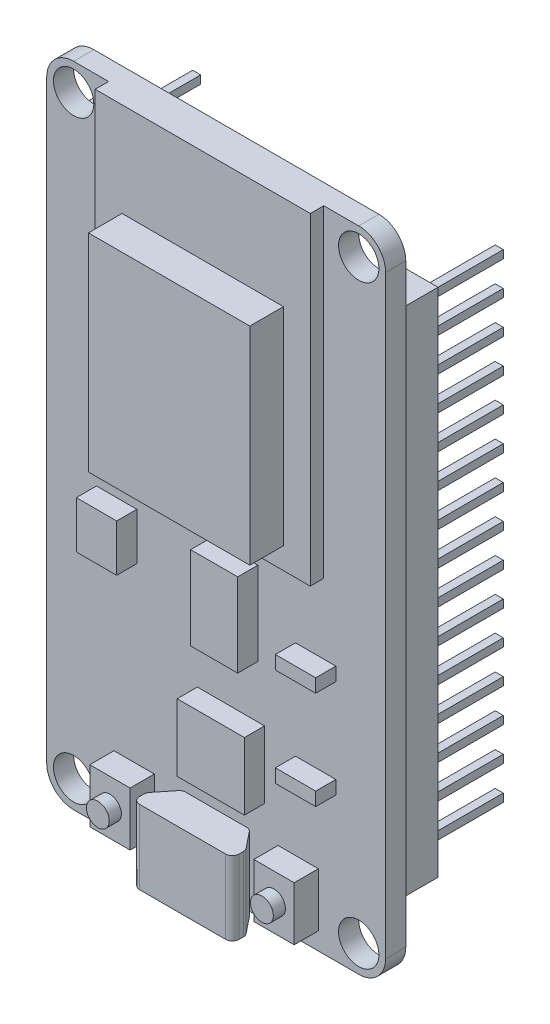
SolidWorks part; units mm, degrees
ref_plane "Plan de face" through (0, 0, 0) normal (0, 0, 1) x (1, 0, 0)
ref_plane "Plan de dessus" through (0, 0, 0) normal (0, 1, 0) x (1, 0, 0)
ref_plane "Plan de droite" through (0, 0, 0) normal (1, 0, 0) x (0, 0, -1)
sketch "Esquisse1" plane through (0, 0, 0) normal (0, 0, 1) x (1, 0, 0)
  line L1 (-10.6, -24.1) -> (10.6, -24.1)
  line L2 (-12.6, -22.1) -> (-12.6, 22.1)
  line L3 (-10.6, 24.1) -> (10.6, 24.1)
  line L4 (12.6, -22.1) -> (12.6, 22.1)
  line L5 (-12.6, -24.1) -> (12.6, 24.1) construction
  line L6 (-12.6, 24.1) -> (12.6, -24.1) construction
  arc A0 (-10.6, -24.1) -> (-12.6, -22.1) centre (-10.6, -22.1) cw
  arc A1 (10.6, -24.1) -> (12.6, -22.1) centre (10.6, -22.1) ccw
  arc A2 (10.6, 24.1) -> (12.6, 22.1) centre (10.6, 22.1) cw
  arc A3 (-12.6, 22.1) -> (-10.6, 24.1) centre (-10.6, 22.1) cw
  circle A4 centre (-10.6, 22.1) radius 1.5
  circle A5 centre (10.6, 22.1) radius 1.5
  circle A6 centre (-10.6, -22.1) radius 1.5
  circle A7 centre (10.6, -22.1) radius 1.5
  point P0 (0, 0)
  dimension "D3" = 2
  dimension "D4" = 3
  dimension "D5" = 3
  dimension "D6" = 3
  dimension "D7" = 3
  dimension "D1" = 48.2
  dimension "D2" = 25.2
extrude "Boss.-Extru.1" add sketch "Esquisse1" along normal blind 1.5
sketch "Esquisse2" plane through (0, 0, 1.5) normal (0, 0, 1) x (1, 0, 0)
  line L0 (10.6, 24.1) -> (-10.6, 24.1) construction
  line L1 (-8, 24.1) -> (8, 24.1)
  line L2 (-8, 24.1) -> (-8, 0.1)
  line L3 (-8, 0.1) -> (8, 0.1)
  line L4 (8, 24.1) -> (8, 0.1)
  point P6 (0, 0.1)
  dimension "D1" = 16
  dimension "D2" = 24
extrude "Boss.-Extru.2" add sketch "Esquisse2" along normal blind 1
sketch "Esquisse3" plane through (0, 0, 2.5) normal (0, 0, 1) x (1, 0, 0)
  line L0 (8, 24.1) -> (-8, 24.1) construction
  line L1 (-6, 1.7) -> (6, 1.7)
  line L2 (-6, 1.7) -> (-6, 17.1)
  line L3 (-6, 17.1) -> (6, 17.1)
  line L4 (6, 1.7) -> (6, 17.1)
  point P6 (0, 1.7)
  dimension "D1" = 12
  dimension "D2" = 15.4
  dimension "D3" = 7
extrude "Boss.-Extru.3" add sketch "Esquisse3" along normal blind 2.5
sketch "Esquisse4" plane through (0, 0, 1.5) normal (0, 0, 1) x (1, 0, 0)
  line L0 (8, 24.1) -> (-8, 24.1) construction
  line L1 (-8.9, -2.4) -> (-5.9, -2.4)
  line L2 (-8.9, -2.4) -> (-8.9, -5.9)
  line L3 (-8.9, -5.9) -> (-5.9, -5.9)
  line L4 (-5.9, -2.4) -> (-5.9, -5.9)
  line L5 (-0.4, -1.5) -> (3.1, -1.5)
  line L6 (-0.4, -1.5) -> (-0.4, -7.7)
  line L7 (-0.4, -7.7) -> (3.1, -7.7)
  line L8 (3.1, -1.5) -> (3.1, -7.7)
  line L9 (-1.4, -11.6) -> (3.6, -11.6)
  line L10 (-1.4, -11.6) -> (-1.4, -16.6)
  line L11 (-1.4, -16.6) -> (3.6, -16.6)
  line L12 (3.6, -11.6) -> (3.6, -16.6)
  line L13 (5.9, -5.1) -> (8.9, -5.1)
  line L14 (5.9, -5.1) -> (5.9, -6.1)
  line L15 (5.9, -6.1) -> (8.9, -6.1)
  line L16 (8.9, -5.1) -> (8.9, -6.1)
  line L17 (5.9, -12.4) -> (8.9, -12.4)
  line L18 (5.9, -12.4) -> (5.9, -13.4)
  line L19 (5.9, -13.4) -> (8.9, -13.4)
  line L20 (8.9, -12.4) -> (8.9, -13.4)
  line L25 (-12.6, 22.1) -> (-12.6, -22.1) construction
  line L26 (12.6, -22.1) -> (12.6, 22.1) construction
  line L27 (-10.6, -24.1) -> (10.6, -24.1) construction
  dimension "D1" = 3
  dimension "D2" = 3.5
  dimension "D3" = 30
  dimension "D4" = 6.7
  dimension "D5" = 3.5
  dimension "D6" = 6.2
  dimension "D7" = 31.8
  dimension "D8" = 13
  dimension "D9" = 5
  dimension "D10" = 5
  dimension "D11" = 12.5
  dimension "D12" = 14
  dimension "D13" = 1
  dimension "D14" = 3
  dimension "D15" = 3
  dimension "D16" = 1
  dimension "D17" = 6.7
  dimension "D18" = 19
  dimension "D19" = 11.7
extrude "Boss.-Extru.4" add sketch "Esquisse4" along normal blind 1.5
sketch "Esquisse5" plane through (0, 0, 1.5) normal (0, 0, 1) x (1, 0, 0)
  line L0 (-10.6, -24.1) -> (10.6, -24.1) construction
  line L1 (-7.6, -18.8) -> (-4.6, -18.8)
  line L2 (-7.6, -18.8) -> (-7.6, -22.8)
  line L3 (-7.6, -22.8) -> (-4.6, -22.8)
  line L4 (-4.6, -18.8) -> (-4.6, -22.8)
  line L5 (-12.6, 22.1) -> (-12.6, -22.1) construction
  dimension "D1" = 3
  dimension "D2" = 4
  dimension "D3" = 5.3
  dimension "D4" = 8
extrude "Boss.-Extru.5" add sketch "Esquisse5" along normal blind 1.8
sketch "Esquisse6" plane through (0, 0, 3.3) normal (0, 0, 1) x (1, 0, 0)
  line L0 (-7.6, -18.8) -> (-7.6, -22.8) construction
  line L2 (-7.6, -22.8) -> (-4.6, -22.8) construction
  circle A0 centre (-6.1, -20.8) radius 0.85
  dimension "D1" = 1.7
  dimension "D2" = 1.5
  dimension "D3" = 2
extrude "Boss.-Extru.6" add sketch "Esquisse6" along normal blind 0.9
mirror "Symétrie1" about plane through (0, 0, 0) normal (1, 0, 0) of "Boss.-Extru.6", "Boss.-Extru.5"
sketch "Esquisse7" plane through (0, -18.8, 0) normal (0, 1, 0) x (1, 0, 0)
  line L0 (0, 0) -> (0, -8.6445) construction
  line L1 (-3.2, -4) -> (3.2, -4)
  line L2 (3.7, -3.5) -> (3.7, -3.1754)
  line L3 (3.5904, -2.863) -> (2.6501, -1.6877)
  line L4 (-1.4, -1.5) -> (3.6, -1.5) construction
  line L5 (2.2597, -1.5) -> (-2.2597, -1.5)
  line L6 (-8, -1.5) -> (8, -1.5) construction
  line L7 (-2.6501, -1.6877) -> (-3.5904, -2.863)
  line L8 (-3.7, -3.1754) -> (-3.7, -3.5)
  line L9 (-10.6, 0) -> (10.6, 0) construction
  arc A0 (3.7, -3.1754) -> (3.5904, -2.863) centre (3.2, -3.1754) ccw
  arc A1 (-3.5904, -2.863) -> (-3.7, -3.1754) centre (-3.2, -3.1754) ccw
  arc A2 (-2.2597, -1.5) -> (-2.6501, -1.6877) centre (-2.2597, -2) ccw
  arc A3 (2.6501, -1.6877) -> (2.2597, -1.5) centre (2.2597, -2) ccw
  arc A4 (3.2, -4) -> (3.7, -3.5) centre (3.2, -3.5) ccw
  arc A5 (-3.2, -4) -> (-3.7, -3.5) centre (-3.2, -3.5) cw
  point P15 (0, -1.5)
  point P16 (0, -4)
  point P19 (3.7, -3)
  point P22 (-3.7, -3)
  point P25 (-2.5, -1.5)
  point P28 (2.5, -1.5)
  point P31 (3.7, -4)
  point P34 (-3.7, -4)
  dimension "D6" = 0.5
  dimension "D1" = 7.4
  dimension "D2" = 4
  dimension "D3" = 5
  dimension "D4" = 1
  dimension "D5" = 1
extrude "Boss.-Extru.7" add sketch "Esquisse7" against normal blind 5.5
sketch "Esquisse8" plane through (0, -24.3, 0) normal (0, -1, 0) x (1, 0, 0)
  line L50 (-2, 3.1) -> (2, 3.1)
  line L51 (-2, 3.1) -> (-2, 2.8)
  line L52 (-2, 2.8) -> (2, 2.8)
  line L53 (2, 3.1) -> (2, 2.8)
  line L55 (-3.5, 3.5) -> (-3.5, 3.1754)
  line L56 (-3.4343, 2.988) -> (-2.4939, 1.8126)
  line L57 (-2.2597, 1.7) -> (2.2597, 1.7)
  line L58 (2.4939, 1.8126) -> (3.4343, 2.988)
  line L59 (3.5, 3.1754) -> (3.5, 3.5)
  line L60 (3.2, 3.8) -> (-3.2, 3.8)
  line L61 (-3.5, 3.5) -> (-3.5, 3.1754)
  line L62 (-3.4343, 2.988) -> (-2.4939, 1.8126)
  line L63 (-2.2597, 1.7) -> (2.2597, 1.7)
  line L64 (2.4939, 1.8126) -> (3.4343, 2.988)
  line L65 (3.5, 3.1754) -> (3.5, 3.5)
  line L66 (3.2, 3.8) -> (-3.2, 3.8)
  arc A46 (-3.2, 3.8) -> (-3.5, 3.5) centre (-3.2, 3.5) ccw
  arc A47 (-3.5, 3.1754) -> (-3.4343, 2.988) centre (-3.2, 3.1754) ccw
  arc A48 (-2.4939, 1.8126) -> (-2.2597, 1.7) centre (-2.2597, 2) ccw
  arc A49 (2.2597, 1.7) -> (2.4939, 1.8126) centre (2.2597, 2) ccw
  arc A50 (3.4343, 2.988) -> (3.5, 3.1754) centre (3.2, 3.1754) ccw
  arc A51 (3.5, 3.5) -> (3.2, 3.8) centre (3.2, 3.5) ccw
  arc A52 (-3.2, 3.8) -> (-3.5, 3.5) centre (-3.2, 3.5) ccw
  arc A53 (-3.5, 3.1754) -> (-3.4343, 2.988) centre (-3.2, 3.1754) ccw
  arc A54 (-2.4939, 1.8126) -> (-2.2597, 1.7) centre (-2.2597, 2) ccw
  arc A55 (2.2597, 1.7) -> (2.4939, 1.8126) centre (2.2597, 2) ccw
  arc A56 (3.4343, 2.988) -> (3.5, 3.1754) centre (3.2, 3.1754) ccw
  arc A57 (3.5, 3.5) -> (3.2, 3.8) centre (3.2, 3.5) ccw
  point P4 (0, 2.8)
  dimension "D2" = 4
  dimension "D3" = 0.3
  dimension "D4" = 0.7
  dimension "D1" = 0.2
extrude "Enlèv. mat.-Extru.1" cut sketch "Esquisse8" against normal blind 4.5
sketch "Esquisse9" plane through (0, 0, 0) normal (0, 0, -1) x (-1, 0, 0)
  line L0 (10.6, -24.1) -> (-10.6, -24.1) construction
  line L1 (-12.5, 19.1) -> (-10, 19.1)
  line L2 (-12.5, 19.1) -> (-12.5, -18.9)
  line L3 (-12.5, -18.9) -> (-10, -18.9)
  line L4 (-10, 19.1) -> (-10, -18.9)
  line L5 (-12.6, -22.1) -> (-12.6, 22.1) construction
  dimension "D1" = 2.5
  dimension "D2" = 38
  dimension "D3" = 5.2
  dimension "D4" = 0.1
extrude "Boss.-Extru.8" add sketch "Esquisse9" along normal blind 2.5
sketch "Esquisse10" plane through (0, 0, -2.5) normal (0, 0, -1) x (-1, 0, 0)
  line L0 (-12.5, 19.1) -> (-12.5, -18.9) construction
  line L1 (-11.55, 17.55) -> (-10.95, 17.55)
  line L2 (-11.55, 17.55) -> (-11.55, 18.15)
  line L3 (-11.55, 18.15) -> (-10.95, 18.15)
  line L4 (-10.95, 17.55) -> (-10.95, 18.15)
  line L5 (-11.55, 17.55) -> (-10.95, 18.15) construction
  line L6 (-11.55, 18.15) -> (-10.95, 17.55) construction
  line L7 (-10, 19.1) -> (-12.5, 19.1) construction
  point P0 (-11.25, 17.85)
  dimension "D1" = 0.6
  dimension "D3" = 1.25
  dimension "D4" = 1.25
extrude "Boss.-Extru.9" add sketch "Esquisse10" along normal blind 5.8
pattern_linear "Répétition linéaire1" count 15 spacing 2.5 along (0, -1, 0) of "Boss.-Extru.9"
mirror "Symétrie2" about plane through (0, 0, 0) normal (1, 0, 0) of "Répétition linéaire1", "Boss.-Extru.8", "Boss.-Extru.9"
